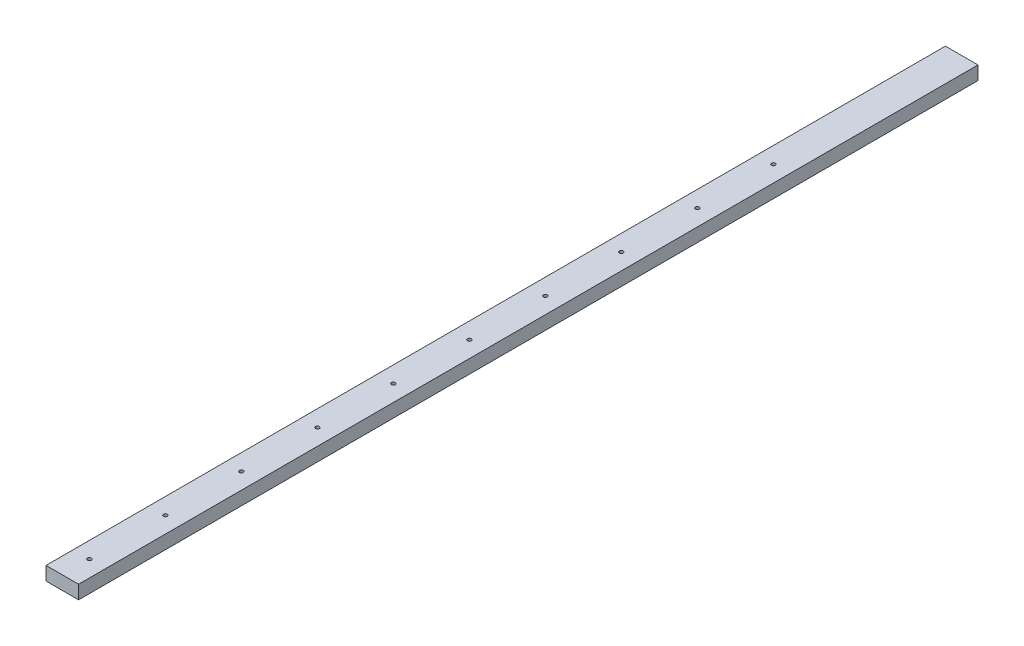
SolidWorks part; units mm, degrees
material "PE1000 Высокой плотности"
ref_plane "Спереди" through (0, 0, 0) normal (0, 0, 1) x (1, 0, 0)
ref_plane "Сверху" through (0, 0, 0) normal (0, 1, 0) x (1, 0, 0)
ref_plane "Справа" through (0, 0, 0) normal (1, 0, 0) x (0, 0, -1)
sketch "Эскиз1" plane through (0, 0, 0) normal (0, 0, 1) x (1, 0, 0)
  line L1 (-30, -12.5) -> (30, -12.5)
  line L2 (-30, -12.5) -> (-30, 12.5)
  line L3 (-30, 12.5) -> (30, 12.5)
  line L4 (30, -12.5) -> (30, 12.5)
  line L5 (-30, -12.5) -> (30, 12.5) construction
  line L6 (-30, 12.5) -> (30, -12.5) construction
  point P0 (0, 0)
  dimension "D1" = 25
  dimension "D2" = 60
extrude "Бобышка-Вытянуть1" add sketch "Эскиз1" along normal blind 1657
sketch "Эскиз2" plane through (0, -12.5, 0) normal (0, -1, 0) x (1, 0, 0)
  line L0 (-30, 0) -> (30, 0) construction
  circle A0 centre (-5, 72) radius 15
  dimension "D1" = 30
  dimension "D2" = 72
extrude "Вырез-Вытянуть1" cut sketch "Эскиз2" against normal blind 10
sketch "Эскиз3" plane through (0, 12.5, 0) normal (0, 1, 0) x (1, 0, 0)
  line L0 (30, 0) -> (-30, 0) construction
  line L1 (0, 0) -> (0, -1607) construction
  line L2 (30, -1657) -> (-30, -1657) construction
  circle A0 centre (0, -1607) radius 3.5
  circle A11 centre (0, -1467) radius 3.5
  circle A12 centre (0, -1327) radius 3.5
  circle A13 centre (0, -1187) radius 3.5
  circle A14 centre (0, -1047) radius 3.5
  circle A15 centre (0, -907) radius 3.5
  circle A16 centre (0, -767) radius 3.5
  circle A17 centre (0, -627) radius 3.5
  circle A18 centre (0, -487) radius 3.5
  circle A19 centre (0, -347) radius 3.5
  dimension "D1" = 50
  dimension "D2" = 7
  dimension "D4" = 140
  dimension "D3" = 10
extrude "Вырез-Вытянуть2" cut sketch "Эскиз3" against normal through all both and the other way through all
